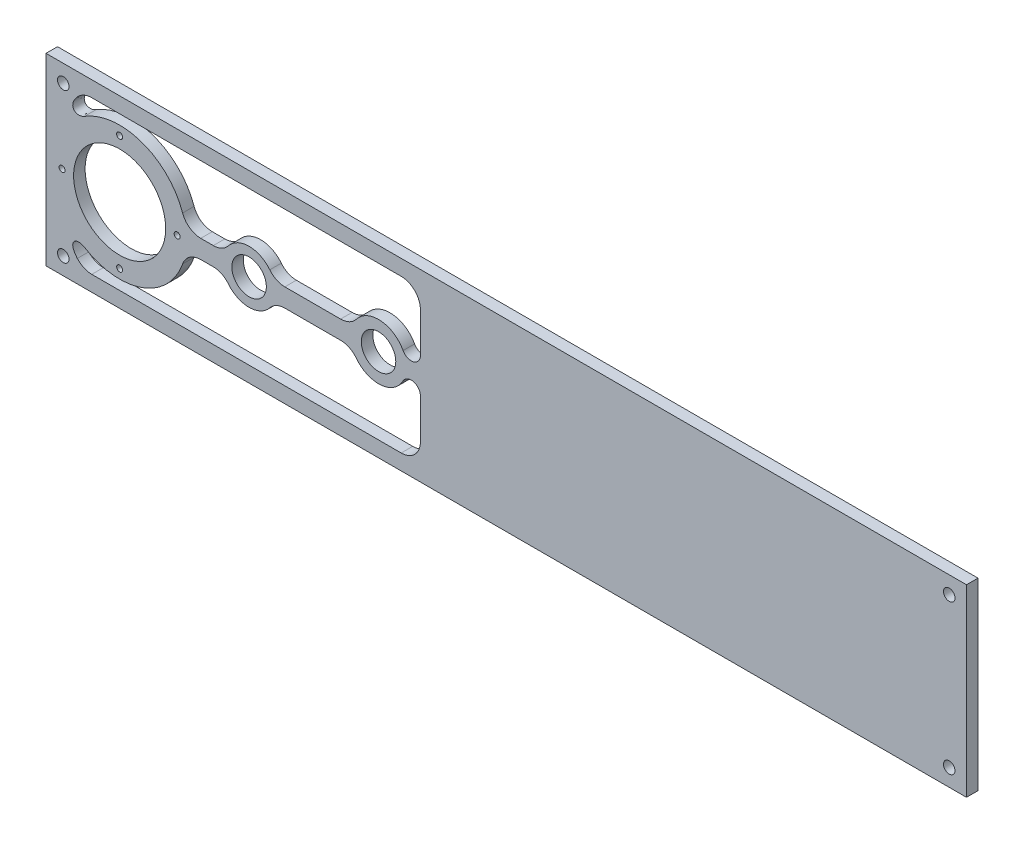
SolidWorks part; units mm, degrees
material "1060 Alloy"
ref_plane "Front Plane" through (0, 0, 0) normal (0, 0, 1) x (1, 0, 0)
ref_plane "Top Plane" through (0, 0, 0) normal (0, 1, 0) x (1, 0, 0)
ref_plane "Right Plane" through (0, 0, 0) normal (1, 0, 0) x (0, 0, -1)
sketch "Sketch1" plane through (0, 0, 0) normal (0, 0, 1) x (1, 0, 0)
  line L1 (0, 50.8) -> (508, 50.8)
  line L2 (0, 50.8) -> (0, -50.8)
  line L3 (0, -50.8) -> (508, -50.8)
  line L4 (508, 50.8) -> (508, -50.8)
  dimension "D1" = 508
  dimension "D2" = 101.6
extrude "Boss-Extrude1" add sketch "Sketch1" against normal blind 6.35
sketch "Sketch2" plane through (0, 0, 0) normal (0, 0, 1) x (1, 0, 0)
  line L0 (0, 50.8) -> (0, -50.8) construction
  circle A0 centre (40.64, 0) radius 25.4
  circle A1 centre (72.39, 0) radius 1.651
  circle A2 centre (40.64, -31.75) radius 1.651
  circle A3 centre (8.89, 0) radius 1.651
  circle A4 centre (40.64, 31.75) radius 1.651
  point P15 (40.64, 0)
  dimension "D1" = 50.8
  dimension "D2" = 3.302
  dimension "D3" = 31.75
  dimension "D4" = 40.64
  dimension "D5" = 4
extrude "Motor mount" cut sketch "Sketch2" against normal blind 6.35
sketch "Sketch3" plane through (0, 0, 0) normal (0, 0, 1) x (1, 0, 0)
  circle A0 centre (40.64, 0) radius 25.4 construction
  circle A1 centre (40.64, 0) radius 25.4 construction
  circle A2 centre (112.0775, 0) radius 9.525
  circle A3 centre (183.515, 0) radius 9.525
  dimension "D1" = 19.05
  dimension "D2" = 19.05
  dimension "D3" = 71.4375
  dimension "D4" = 71.4375
extrude "Cut-Extrude2" cut sketch "Sketch3" against normal through all
sketch "Sketch4" plane through (0, 0, 0) normal (0, 0, 1) x (1, 0, 0)
  line L0 (508, 50.8) -> (0, 50.8) construction
  line L1 (0, 50.8) -> (0, -50.8) construction
  line L2 (508, -50.8) -> (508, 50.8) construction
  line L3 (0, -50.8) -> (508, -50.8) construction
  circle A0 centre (9.525, 41.275) radius 3.175
  circle A1 centre (9.525, -41.275) radius 3.175
  circle A2 centre (498.475, 41.275) radius 3.175
  circle A3 centre (498.475, -41.275) radius 3.175
  dimension "D1" = 6.35
  dimension "D2" = 6.35
  dimension "D3" = 6.35
  dimension "D4" = 6.35
  dimension "D5" = 9.525
  dimension "D6" = 9.525
  dimension "D7" = 9.525
  dimension "D8" = 9.525
extrude "Cut-Extrude3" cut sketch "Sketch4" against normal through all
sketch "Sketch7" plane through (0, 0, 0) normal (0, 0, 1) x (1, 0, 0)
  line L3 (211.7063, 0) -> (211.7063, 47.2876) construction
  line L5 (211.7063, 47.2876) -> (0, 47.2876) construction
  line L6 (0, 47.2876) -> (0, 0) construction
  line L7 (0, 0) -> (40.64, 0) construction
  line L8 (40.64, -5.08) -> (112.0775, -5.08)
  line L9 (112.0775, -5.08) -> (183.515, -5.08)
  line L10 (183.515, -5.08) -> (216.7863, -5.08)
  line L11 (216.7863, -5.08) -> (216.7863, 52.3676)
  line L12 (216.7863, 52.3676) -> (-5.08, 52.3676)
  line L13 (-5.08, 52.3676) -> (-5.08, -5.08)
  line L14 (-5.08, -5.08) -> (40.64, -5.08)
  line L15 (85.4063, 5.08) -> (92.3414, 5.08)
  line L16 (131.8136, 5.08) -> (162.5851, 5.08)
  line L18 (206.6263, 9.6628) -> (206.6263, 31.6032)
  line L19 (196.0219, 42.2076) -> (25.2631, 42.2076)
  line L20 (0, 50.8) -> (0, -50.8) construction
  line L22 (206.6263, 5.08) -> (206.6263, 42.2076) construction
  line L23 (112.0775, 5.08) -> (183.515, 5.08) construction
  line L24 (40.64, 5.08) -> (112.0775, 5.08) construction
  line L25 (206.6263, 42.2076) -> (5.08, 42.2076) construction
  line L26 (5.08, 42.2076) -> (5.08, 5.08) construction
  line L27 (112.0775, 0) -> (183.515, 0) construction
  line L28 (40.64, 0) -> (112.0775, 0) construction
  line L29 (183.515, 0) -> (211.7063, 0) construction
  line L30 (5.08, 5.08) -> (40.64, 5.08) construction
  line L31 (183.515, 5.08) -> (206.6263, 5.08) construction
  circle A0 centre (40.64, 0) radius 31.75 construction
  circle A1 centre (112.0775, 0) radius 9.525
  circle A2 centre (183.515, 0) radius 9.525
  circle A3 centre (9.525, 41.275) radius 3.1307
  arc A4 (100.6434, 9.0867) -> (92.3414, 5.08) centre (92.3414, 15.6844) cw
  arc A5 (197.0687, 7.2633) -> (206.6263, 9.6628) centre (201.5463, 9.6628) ccw
  arc A6 (17.2833, 38.5871) -> (25.2631, 42.2076) centre (25.2631, 31.6032) cw
  arc A7 (206.6263, 31.6032) -> (196.0219, 42.2076) centre (196.0219, 31.6032) ccw
  circle A8 centre (112.0775, 0) radius 4.445
  circle A9 centre (183.515, 0) radius 4.445
  circle A10 centre (40.64, 0) radius 26.67
  arc A11 (197.0687, 7.2633) -> (171.333, 9.3838) centre (183.515, 0) ccw
  arc A12 (162.5851, 5.08) -> (171.333, 9.3838) centre (162.5851, 16.1223) ccw
  arc A13 (123.5116, 9.0867) -> (100.6434, 9.0867) centre (112.0775, 0) ccw
  arc A14 (131.8136, 5.08) -> (123.5116, 9.0867) centre (131.8136, 15.6844) cw
  arc A15 (75.3984, 12.178) -> (21.2634, 31.3209) centre (40.64, 0) ccw
  arc A17 (75.3984, 12.178) -> (85.4063, 5.08) centre (85.4063, 15.6844) ccw
  spline S0 degree 3 poles (17.2833, 38.5871) (11.5305, 32.014) (16.7871, 28.5516) (21.2634, 31.3209) knots 0 0 0 0 1 1 1 1
  point P9 (0, 0)
  dimension "D1" = 5.08
  dimension "D3" = 5.08
  dimension "D4" = 11.0423
  dimension "D5" = 10.6044
  dimension "D6" = 10.6044
  dimension "D7" = 10.6044
  dimension "D2" = 5.08
extrude "Cut-Extrude4" cut sketch "Sketch7" against normal through all contours L19 A6 S0 A15 A17 L15 A4 A13 A14 L16 A12 A11 A5 L18 A7
mirror "Mirror1" about plane through (0, 0, 0) normal (0, 1, 0) of "Cut-Extrude4"
